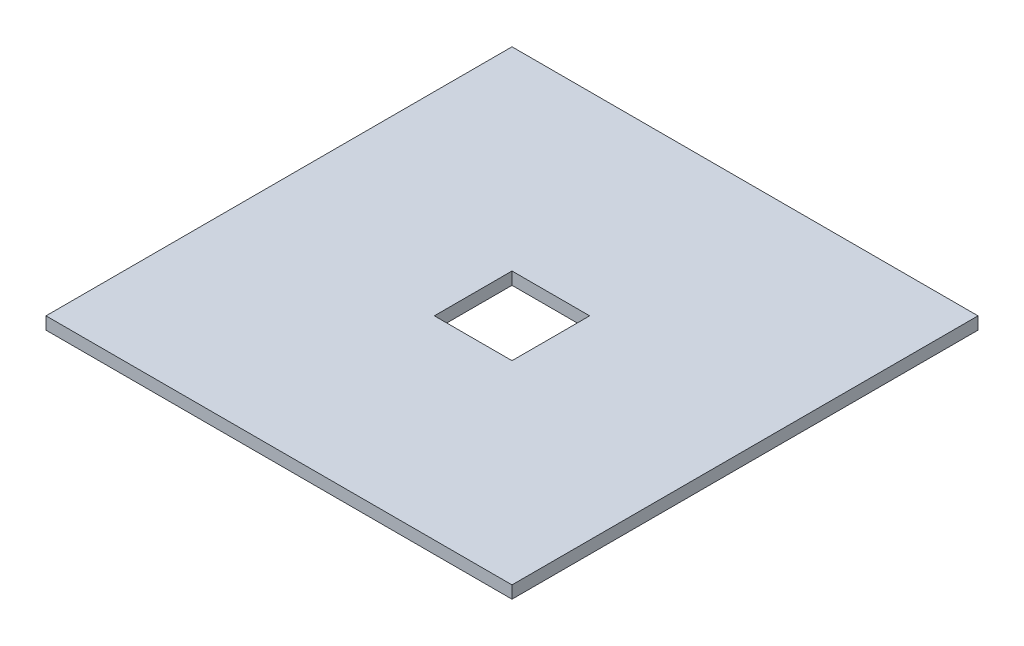
SolidWorks part; units mm, degrees
ref_plane "Front Plane" through (0, 0, 0) normal (0, 0, 1) x (1, 0, 0)
ref_plane "Top Plane" through (0, 0, 0) normal (0, 1, 0) x (1, 0, 0)
ref_plane "Right Plane" through (0, 0, 0) normal (1, 0, 0) x (0, 0, -1)
sketch "Sketch1" plane through (0, 0, 0) normal (0, 1, 0) x (1, 0, 0)
  line L1 (-150, -150) -> (150, -150)
  line L2 (-150, -150) -> (-150, 150)
  line L3 (-150, 150) -> (150, 150)
  line L4 (150, -150) -> (150, 150)
  line L5 (-150, -150) -> (150, 150) construction
  line L6 (-150, 150) -> (150, -150) construction
  point P0 (0, 0)
  dimension "D1" = 300
  dimension "D2" = 300
extrude "Boss-Extrude1" add sketch "Sketch1" along normal blind 8
sketch "Sketch2" plane through (0, 8, 0) normal (0, 1, 0) x (1, 0, 0)
  line L1 (-25, -25) -> (25, -25)
  line L2 (-25, -25) -> (-25, 25)
  line L3 (-25, 25) -> (25, 25)
  line L4 (25, -25) -> (25, 25)
  line L5 (-25, -25) -> (25, 25) construction
  line L6 (-25, 25) -> (25, -25) construction
  point P0 (0, 0)
  dimension "D1" = 50
  dimension "D2" = 50
extrude "Cut-Extrude1" cut sketch "Sketch2" against normal blind 10
